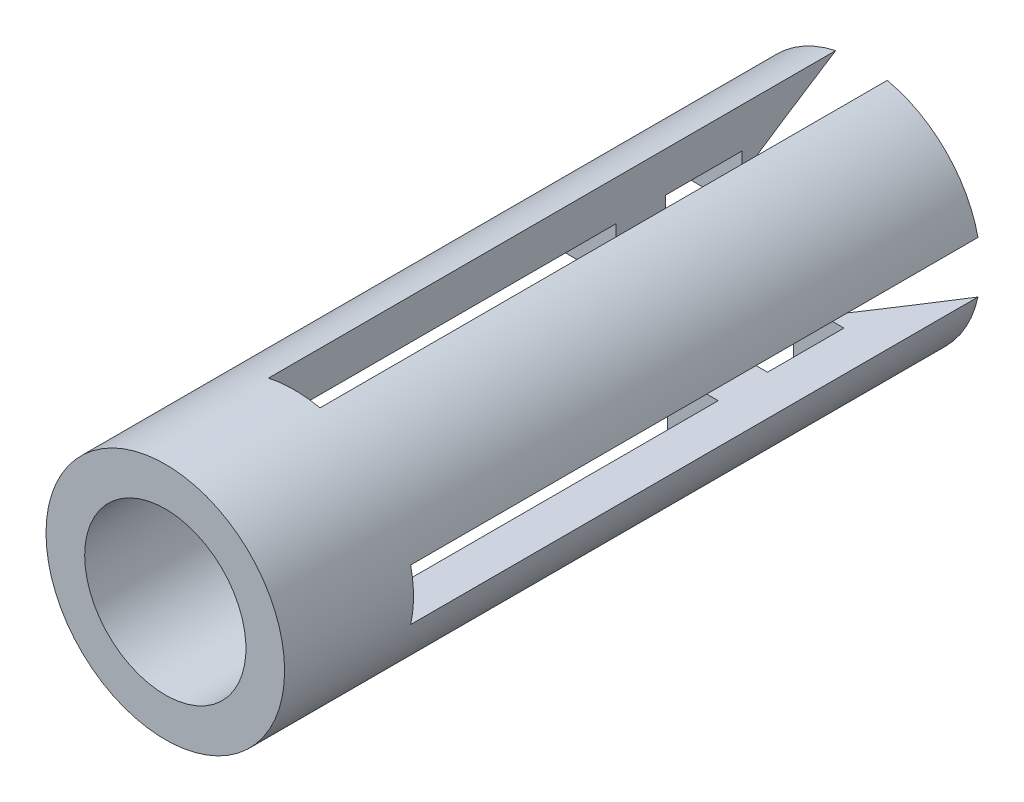
SolidWorks part; units mm, degrees
ref_plane "Front Plane" through (0, 0, 0) normal (1, 0, 0) x (0, 1, 0)
ref_plane "Top Plane" through (0, 0, 0) normal (0, 0, 1) x (0, 1, 0)
ref_plane "Right Plane" through (0, 0, 0) normal (0, 1, 0) x (-1, 0, 0)
ref_axis "Axis1" through (0, 0, -23.8856) along (0, 0, 1)
sketch "Sketch4" plane through (0, 0, 0) normal (1, 0, 0) x (0, 1, 0)
  line L0 (11.7538, 15.4982) -> (11.7538, 84.0905)
  line L1 (11.7538, 84.0905) -> (7.9439, 84.0905)
  line L2 (7.9439, 84.0905) -> (7.9439, 37.1392)
  line L3 (7.9439, 37.1392) -> (3.2587, 37.1392)
  line L4 (3.2587, 37.1392) -> (3.2587, 32.2839)
  line L5 (3.2587, 32.2839) -> (7.9438, 32.2839)
  line L6 (7.9438, 32.2839) -> (7.9439, 24.7528)
  line L7 (7.9439, 24.7528) -> (5.969, 24.7528)
  line L8 (5.969, 24.7528) -> (11.7538, 15.4982)
  line L9 (0, -55) -> (0, 55) construction
  point P6 (0, 0)
  point P10 (0, 0)
  point P11 (0, 0)
  dimension "D1" = 7.5311
  dimension "D2" = 5.969
  dimension "D3" = 7.9438
  dimension "D4" = 3.81
  dimension "D5" = 3.81
  dimension "D6" = 68.5923
revolve "Revolve1" add sketch "Sketch4" angle 360 about axis through (0, 0, -23.8856) along (0, 0, 1)
sketch "Sketch7" plane through (0, 0, 0) normal (1, 0, 0) x (0, 1, 0)
  line L0 (11.7538, 15.4982) -> (-11.7538, 15.4982) construction
  line L1 (-2.54, 15.4982) -> (2.54, 15.4982)
  line L2 (-2.54, 15.4982) -> (-2.54, 71.3905)
  line L3 (-2.54, 71.3905) -> (2.54, 71.3905)
  line L4 (2.54, 15.4982) -> (2.54, 71.3905)
  line L5 (0, -12.9292) -> (0, 12.9292) construction
  point P8 (0, 71.3905)
  dimension "D1" = 55.8923
  dimension "D2" = 5.08
extrude "Cut-Extrude1" cut sketch "Sketch7" against normal through all both and the other way through all
sketch "Sketch8" plane through (0, 0, 0) normal (0, 1, 0) x (-1, 0, 0)
  line L0 (11.4761, 15.4982) -> (-11.4761, 15.4982) construction
  line L1 (-2.54, 15.4982) -> (2.54, 15.4982)
  line L2 (-2.54, 15.4982) -> (-2.54, 71.3905)
  line L3 (-2.54, 71.3905) -> (2.54, 71.3905)
  line L4 (2.54, 15.4982) -> (2.54, 71.3905)
  line L5 (0, 12.9292) -> (0, -12.9292) construction
  point P6 (0, 71.3905)
  dimension "D1" = 55.8923
  dimension "D2" = 5.08
extrude "Cut-Extrude2" cut sketch "Sketch8" against normal through all both and the other way through all
equation "\"BULB_D\"= 0.6255'The Measured Diameter of the larger section of the Motor Shaft (in)"
equation "\"SHAFT_D\"= 0.47'The measured diameter of the thinner section of the Motor shaft (in)"
equation "\"BULB_H\"= 0.2965'The measured height of the larger section of the Motor shaft (in)"
equation "\"TOL\"= 0.025'Unused Tolerance Variable in case of iterations or design failure (in)"
equation "\"D1@Sketch4\"=\"BULB_H\""
equation "\"D2@Sketch4\"=\"SHAFT_D\"/2"
equation "\"D3@Sketch4\"=\"BULB_D\"/2"
equation "\"THICK\"= 0.15'The assumed thickness of the sketch for the snap fit (in)"
equation "\"BASE\"= ( \"BULB_D\" + \"THICK\" ) * ( pi / 2 )'The calculated value for the Base, used within the Length calc (in)"
equation "\"ELONG\"= 200000'The assumed Modulus of Elasticity (PSI)"
equation "\"DEFL\"= ( \"BULB_D\" - \"SHAFT_D\" ) / 2'Calculated defelection for a perfect fit on the motor shaft (in)"
equation "\"FORCE\"= 1.5'The Assumed force applied to the beam when being snap fitted (lbf)"
equation "\"LENGTH\"= ( ( \"BASE\" * \"ELONG\" * \"THICK\" ^ 3 * \"DEFL\" ) / ( 4 * \"FORCE\" ) ) ^ ( 1 / 3 )'The calculated length for the required deflection (in)"
equation "\"OFFSET\"= 0.5'Value added to Length to give model rigid body to deflect off of (in)"
equation "\"D4@Sketch4\"=\"THICK\""
equation "\"D5@Sketch4\"=\"THICK\""
equation "\"D6@Sketch4\"=\"LENGTH\" + \"OFFSET\""
equation "\"D1@Sketch7\"=\"LENGTH\""
equation "\"D1@Sketch8\"=\"LENGTH\""
